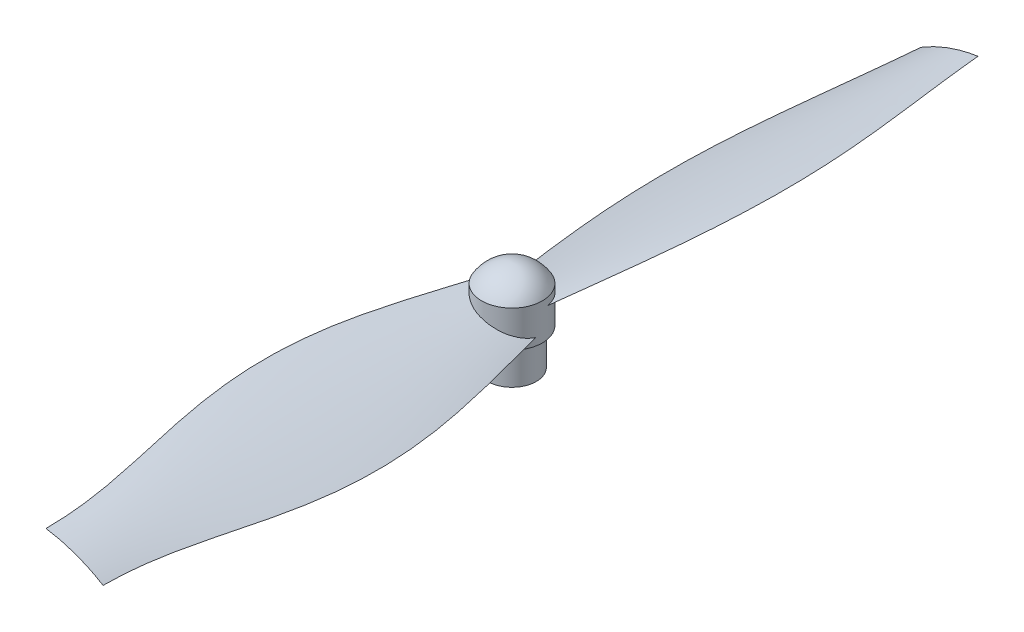
SolidWorks part; units mm, degrees
ref_plane "Front Plane" through (0, 0, 0) normal (0, 0, 1) x (1, 0, 0)
ref_plane "Top Plane" through (0, 0, 0) normal (0, 1, 0) x (1, 0, 0)
ref_plane "Right Plane" through (0, 0, 0) normal (1, 0, 0) x (0, 0, -1)
sketch "Sketch1" plane through (0, 0, 0) normal (0, 0, 1) x (1, 0, 0)
  line L0 (0, 0) -> (0, 15)
  line L1 (0, 0) -> (4, 0)
  line L2 (4, 0) -> (4, 6)
  line L3 (4, 6) -> (5, 6)
  line L4 (5, 6) -> (5, 12)
  arc A0 (0, 15) -> (5, 12) centre (-0.198, 9.0033) cw
  dimension "D6" = 6
  dimension "D1" = 15
  dimension "D2" = 4
  dimension "D3" = 6
  dimension "D4" = 1
  dimension "D5" = 6
revolve "Revolve1" add sketch "Sketch1" angle 360 about L0
sketch "Sketch2" plane through (0, 0, 0) normal (0, -1, 0) x (1, 0, 0)
  line L1 (2.8868, 0) -> (1.4434, 2.5)
  line L2 (1.4434, 2.5) -> (-1.4434, 2.5)
  line L3 (-1.4434, 2.5) -> (-2.8868, 0)
  line L4 (-2.8868, 0) -> (-1.4434, -2.5)
  line L5 (-1.4434, -2.5) -> (1.4434, -2.5)
  line L6 (1.4434, -2.5) -> (2.8868, 0)
  circle A0 centre (0, 0) radius 2.5 construction
  dimension "D1" = 5
extrude "Cut-Extrude1" cut sketch "Sketch2" against normal blind 7
ref_plane "Plane1" through (0, 0, 20) normal (0, 0, 1) x (1, 0, 0)
ref_plane "Plane2" through (0, 0, 72) normal (0, 0, 1) x (1, 0, 0)
sketch "Sketch4" plane through (0, 0, 0) normal (0, 0, 1) x (1, 0, 0)
  line L0 (0, 0) -> (0, 15) construction
  line L1 (-4.6985, 10.7101) -> (4.6985, 7.2899) construction
  line L2 (-4, 0) -> (4, 0) construction
  arc A0 (-4.6985, 10.7101) -> (4.6985, 7.2899) centre (-8.3777, -14.0177) cw
  point P7 (0, 9)
  dimension "D4" = 25
  dimension "D1" = 10
  dimension "D2" = 70
  dimension "D3" = 9
sketch "Sketch5" plane through (0, 0, 20) normal (0, 0, 1) x (1, 0, 0)
  line L0 (0, 0) -> (0, 15) construction
  line L1 (-8.4572, 12.0782) -> (8.4572, 5.9218) construction
  arc A0 (-8.4572, 12.0782) -> (8.4572, 5.9218) centre (-27.1879, -65.6982) cw
  point P7 (0, 9)
  dimension "D4" = 80
  dimension "D1" = 18
  dimension "D2" = 70
  dimension "D3" = 9
sketch "Sketch6" plane through (0, 0, 72) normal (0, 0, 1) x (1, 0, 0)
  line L0 (0, 0) -> (0, 15) construction
  line L1 (-4.6985, 10.7101) -> (4.6985, 7.2899) construction
  line L2 (-4, 0) -> (4, 0) construction
  arc A0 (-4.6985, 10.7101) -> (4.6985, 7.2899) centre (-8.3777, -14.0177) cw
  point P7 (0, 9)
  dimension "D4" = 25
  dimension "D1" = 10
  dimension "D2" = 70
  dimension "D3" = 9
surface "Surface-Loft1"
ref_plane "Plane3" through (0, 0, -20) normal (0, 0, -1) x (-1, 0, 0)
ref_plane "Plane4" through (0, 0, -72) normal (0, 0, 1) x (1, 0, 0)
sketch "Sketch7" plane through (0, 0, 0) normal (0, 0, 1) x (1, 0, 0)
  line L0 (0, 0) -> (0, 15) construction
  line L1 (4.6985, 10.7101) -> (-4.6985, 7.2899)
  line L2 (-4, 0) -> (4, 0) construction
  arc A0 (4.6985, 10.7101) -> (-4.6985, 7.2899) centre (8.3777, -14.0177) ccw
  point P7 (0, 9)
  dimension "D4" = 25
  dimension "D1" = 10
  dimension "D2" = 70
  dimension "D3" = 9
sketch "Sketch8" plane through (0, 0, -20) normal (0, 0, -1) x (-1, 0, 0)
  line L0 (0, 0) -> (0, 15) construction
  line L1 (8.4572, 12.0782) -> (-8.4572, 5.9218)
  line L2 (-4, 0) -> (4, 0) construction
  point P7 (0, 9)
  dimension "D1" = 18
  dimension "D2" = 70
  dimension "D3" = 9
sketch "Sketch9" plane through (0, 0, -72) normal (0, 0, 1) x (1, 0, 0)
  line L0 (0, 0) -> (0, 15) construction
  line L1 (4.6985, 10.7101) -> (-4.6985, 7.2899)
  line L2 (-4, 0) -> (4, 0) construction
  arc A0 (4.6985, 10.7101) -> (-4.6985, 7.2899) centre (8.3777, -14.0177) ccw
  point P7 (0, 9)
  dimension "D4" = 25
  dimension "D1" = 10
  dimension "D2" = 70
  dimension "D3" = 9
sketch "Sketch12" plane through (0, 0, -20) normal (0, 0, -1) x (-1, 0, 0)
  line L0 (0, 0) -> (0, 15) construction
  line L1 (-8.4572, 12.0782) -> (8.4572, 5.9218)
  line L2 (-4, 0) -> (4, 0) construction
  arc A0 (-8.4572, 12.0782) -> (8.4572, 5.9218) centre (-27.1879, -65.6982) cw
  point P7 (0, 9)
  dimension "D4" = 80
  dimension "D1" = 18
  dimension "D2" = 70
  dimension "D3" = 9
surface "Surface-Loft2"
